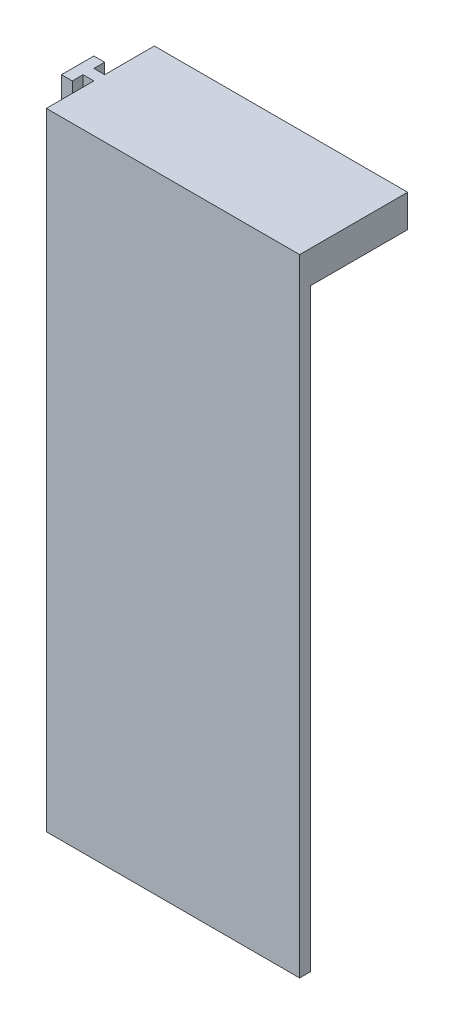
SolidWorks part; units mm, degrees
ref_plane "前基準面" through (0, 0, 0) normal (0, 0, 1) x (1, 0, 0)
ref_plane "上基準面" through (0, 0, 0) normal (0, 1, 0) x (1, 0, 0)
ref_plane "右基準面" through (0, 0, 0) normal (1, 0, 0) x (0, 0, -1)
sketch "草圖1" plane through (0, 0, 0) normal (0, 1, 0) x (1, 0, 0)
  line L1 (-11.725, 5) -> (11.725, 5)
  line L2 (-11.725, 5) -> (-11.725, -5)
  line L3 (-11.725, -5) -> (11.725, -5)
  line L4 (11.725, 5) -> (11.725, -5)
  line L5 (-11.725, 5) -> (11.725, -5) construction
  line L6 (-11.725, -5) -> (11.725, 5) construction
  point P0 (0, 0)
  dimension "D1" = 23.45
  dimension "D2" = 10
extrude "填料-伸長1" add sketch "草圖1" along normal blind 58
sketch "草圖3" plane through (0, 58, 0) normal (0, 1, 0) x (1, 0, 0)
  line L1 (-11.725, 5) -> (-11.725, -5) construction
  line L2 (-11.725, 0.4) -> (-12.725, 0.4)
  line L3 (-12.725, 0.4) -> (-12.725, 1.4)
  line L4 (-12.725, 1.4) -> (-13.725, 1.4)
  line L5 (-13.725, 1.4) -> (-13.725, -1.6001)
  line L6 (-13.725, -1.6001) -> (-12.725, -1.6001)
  line L7 (-12.725, -1.6001) -> (-12.725, -0.6)
  line L8 (-12.725, -0.6) -> (-11.725, -0.6)
  line L9 (-11.725, -0.6) -> (-11.725, 0.4)
extrude "填料-伸長2" add sketch "草圖3" against normal blind 58
sketch "草圖5" plane through (0, 0, -5) normal (0, 0, -1) x (-1, 0, 0)
  line L0 (-11.725, 0) -> (11.725, 0) construction
  line L1 (11.625, 0) -> (-11.725, 0)
  line L2 (11.625, 0) -> (11.625, 55)
  line L3 (11.625, 55) -> (-11.725, 55)
  line L4 (-11.725, 0) -> (-11.725, 55)
  line L5 (-11.725, 58) -> (-11.725, 0) construction
  line L6 (11.725, 58) -> (11.725, 0) construction
  line L7 (-11.725, 58) -> (11.725, 58) construction
  dimension "D1" = 0.1
  dimension "D2" = 3
extrude "除料-伸長2" cut sketch "草圖5" against normal blind 9.01
